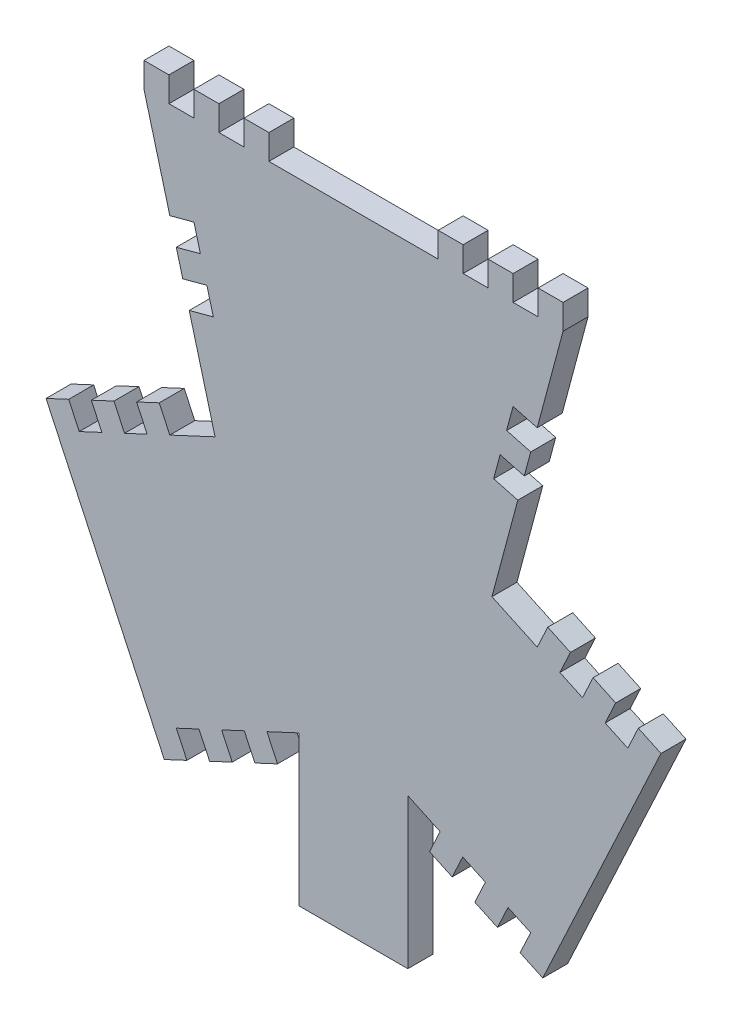
SolidWorks part; units mm, degrees
ref_plane "Plan de face" through (0, 0, 0) normal (0, 0, 1) x (1, 0, 0)
ref_plane "Plan de dessus" through (0, 0, 0) normal (0, 1, 0) x (1, 0, 0)
ref_plane "Plan de droite" through (0, 0, 0) normal (1, 0, 0) x (0, 0, -1)
sketch "Esquisse1" plane through (0, 0, 0) normal (0, 0, 1) x (1, 0, 0)
  line L2 (-88.082, 23.7881) -> (-84.1998, 9.2993)
  line L3 (-88.082, 23.7881) -> (-83.2523, 25.0818)
  line L4 (-84.5464, 29.9114) -> (-83.2523, 25.0818)
  line L5 (-89.3761, 28.6178) -> (-84.5464, 29.9114)
  line L6 (-89.3761, 28.6178) -> (-90.6702, 33.4474)
  line L7 (-90.6702, 33.4474) -> (-85.8405, 34.741)
  line L8 (-87.1341, 39.5708) -> (-85.8405, 34.741)
  line L9 (-91.9639, 38.2771) -> (-87.1341, 39.5708)
  line L10 (-91.9639, 38.2771) -> (-97.1403, 57.5957)
  line L12 (-84.1998, -32.4235) -> (-84.1998, 66.7073) construction
  line L13 (-55.1998, 76.3149) -> (-55.1998, -13.2129) construction
  line L16 (-26.1998, -32.4235) -> (-26.1998, 66.7073) construction
  line L18 (-18.4356, 38.2771) -> (-13.2593, 57.5957)
  line L19 (-18.4356, 38.2771) -> (-23.2654, 39.5708)
  line L20 (-23.2654, 39.5708) -> (-24.559, 34.741)
  line L21 (-19.7293, 33.4474) -> (-24.559, 34.741)
  line L22 (-21.0234, 28.6178) -> (-19.7293, 33.4474)
  line L23 (-21.0234, 28.6178) -> (-25.8531, 29.9114)
  line L24 (-25.8531, 29.9114) -> (-27.1472, 25.0818)
  line L25 (-22.3175, 23.7881) -> (-27.1472, 25.0818)
  line L26 (-22.3175, 23.7881) -> (-26.1998, 9.2993)
  line L29 (-97.1403, 57.5957) -> (-97.1403, 62.5957)
  line L30 (-97.1403, 62.5957) -> (-92.1403, 62.5957)
  line L31 (-92.1403, 62.5957) -> (-92.1403, 57.5957)
  line L32 (-92.1403, 57.5957) -> (-87.1403, 57.5957)
  line L33 (-87.1403, 57.5957) -> (-87.1403, 62.5957)
  line L34 (-87.1403, 62.5957) -> (-82.1403, 62.5957)
  line L35 (-82.1403, 62.5957) -> (-82.1403, 57.5957)
  line L36 (-82.1403, 57.5957) -> (-77.1403, 57.5957)
  line L37 (-77.1403, 57.5957) -> (-77.1403, 62.5957)
  line L38 (-77.1403, 62.5957) -> (-72.1403, 62.5957)
  line L39 (-72.1403, 62.5957) -> (-72.1403, 57.5957)
  line L40 (-72.1403, 57.5957) -> (-38.2593, 57.5957)
  line L41 (-38.2593, 62.5957) -> (-38.2593, 57.5957)
  line L42 (-33.2593, 62.5957) -> (-38.2593, 62.5957)
  line L43 (-33.2593, 57.5957) -> (-33.2593, 62.5957)
  line L44 (-28.2593, 57.5957) -> (-33.2593, 57.5957)
  line L45 (-28.2593, 62.5957) -> (-28.2593, 57.5957)
  line L46 (-23.2593, 62.5957) -> (-28.2593, 62.5957)
  line L47 (-23.2593, 57.5957) -> (-23.2593, 62.5957)
  line L48 (-18.2593, 57.5957) -> (-23.2593, 57.5957)
  line L49 (-18.2593, 62.5957) -> (-18.2593, 57.5957)
  line L50 (-13.2593, 62.5957) -> (-18.2593, 62.5957)
  line L51 (-13.2593, 57.5957) -> (-13.2593, 62.5957)
  line L52 (-92.1403, 57.5957) -> (-96.8053, 56.3457) construction
  line L54 (-66.0739, -38.437) -> (-66.0739, -68.437)
  line L56 (-116.7395, -5.7905) -> (-93.0729, -56.5437)
  line L62 (-84.1998, 9.2993) -> (-26.1998, 9.2993) construction
  line L63 (-116.7395, -5.7905) -> (-112.208, -3.6774)
  line L64 (-112.208, -3.6774) -> (-110.0949, -8.2089)
  line L65 (-110.0949, -8.2089) -> (-105.5634, -6.0958)
  line L66 (-105.5634, -6.0958) -> (-107.6765, -1.5643)
  line L67 (-107.6765, -1.5643) -> (-103.1449, 0.5488)
  line L68 (-103.1449, 0.5488) -> (-101.0318, -3.9827)
  line L69 (-101.0318, -3.9827) -> (-96.5003, -1.8697)
  line L70 (-96.5003, -1.8697) -> (-98.6134, 2.6619)
  line L71 (-98.6134, 2.6619) -> (-94.0818, 4.775)
  line L72 (-94.0818, 4.775) -> (-91.9687, 0.2434)
  line L73 (-91.9687, 0.2434) -> (-82.9057, 4.4696)
  line L74 (-82.9057, 4.4696) -> (-84.1998, 9.2993)
  line L75 (-104.9062, -31.1671) -> (-110.3147, -33.6891) construction
  line L76 (-70.4152, -45.9783) -> (-72.5283, -41.4467)
  line L77 (-74.9468, -48.0913) -> (-70.4152, -45.9783)
  line L78 (-77.0598, -43.5598) -> (-74.9468, -48.0913)
  line L79 (-81.5914, -45.6729) -> (-77.0598, -43.5598)
  line L80 (-79.4783, -50.2044) -> (-81.5914, -45.6729)
  line L81 (-84.0098, -52.3175) -> (-79.4783, -50.2044)
  line L82 (-86.1229, -47.786) -> (-84.0098, -52.3175)
  line L83 (-90.6545, -49.8991) -> (-86.1229, -47.786)
  line L84 (-88.5414, -54.4306) -> (-90.6545, -49.8991)
  line L85 (-93.0729, -56.5437) -> (-88.5414, -54.4306)
  line L87 (-66.0739, -38.437) -> (-72.5283, -41.4467)
  line L88 (-5.4933, -31.1671) -> (-0.0849, -33.6891) construction
  line L89 (-66.0739, -68.437) -> (-44.3256, -68.437)
  line L90 (-26.1998, -32.4235) -> (-26.1998, 66.7073) construction
  line L91 (-44.3256, -38.437) -> (-37.8712, -41.4467)
  line L92 (-21.8582, -54.4306) -> (-19.7451, -49.8991)
  line L93 (-19.7451, -49.8991) -> (-24.2766, -47.786)
  line L94 (-24.2766, -47.786) -> (-26.3897, -52.3175)
  line L95 (-26.3897, -52.3175) -> (-30.9212, -50.2044)
  line L96 (-30.9212, -50.2044) -> (-28.8081, -45.6729)
  line L97 (-28.8081, -45.6729) -> (-33.3397, -43.5598)
  line L98 (-33.3397, -43.5598) -> (-35.4528, -48.0913)
  line L99 (-35.4528, -48.0913) -> (-39.9843, -45.9783)
  line L100 (-39.9843, -45.9783) -> (-37.8712, -41.4467)
  line L101 (-18.4308, 0.2434) -> (-27.4939, 4.4696)
  line L102 (-16.3177, 4.775) -> (-18.4308, 0.2434)
  line L103 (-11.7861, 2.6619) -> (-16.3177, 4.775)
  line L104 (-13.8992, -1.8697) -> (-11.7861, 2.6619)
  line L105 (-9.3677, -3.9827) -> (-13.8992, -1.8697)
  line L106 (-7.2546, 0.5488) -> (-9.3677, -3.9827)
  line L107 (-2.7231, -1.5643) -> (-7.2546, 0.5488)
  line L108 (-4.8362, -6.0958) -> (-2.7231, -1.5643)
  line L109 (-0.3046, -8.2089) -> (-4.8362, -6.0958)
  line L110 (1.8085, -3.6774) -> (-0.3046, -8.2089)
  line L111 (6.34, -5.7905) -> (1.8085, -3.6774)
  line L112 (6.34, -5.7905) -> (-17.3266, -56.5437)
  line L113 (-17.3266, -56.5437) -> (-21.8582, -54.4306)
  line L114 (-27.4939, 4.4696) -> (-26.1998, 9.2993)
  line L115 (-44.3256, -68.437) -> (-44.3256, -38.437)
  point P23 (-55.1998, 57.5957)
  point P46 (-55.1998, 57.5957)
  point P84 (-55.1998, -38.533)
  dimension "D1" = 5
  dimension "D2" = 15
  dimension "D3" = 46
  dimension "D4" = 5
  dimension "D5" = 5
  dimension "D6" = 50
  dimension "D7" = 29
  dimension "D8" = 5
  dimension "D9" = 20
  dimension "D10" = 18.7059
  dimension "D11" = 10
  dimension "D12" = 5
  dimension "D13" = 5
  dimension "D14" = 5
  dimension "D15" = 5
  dimension "D16" = 30
extrude "Boss.-Extru.1" add sketch "Esquisse1" along normal blind 5
